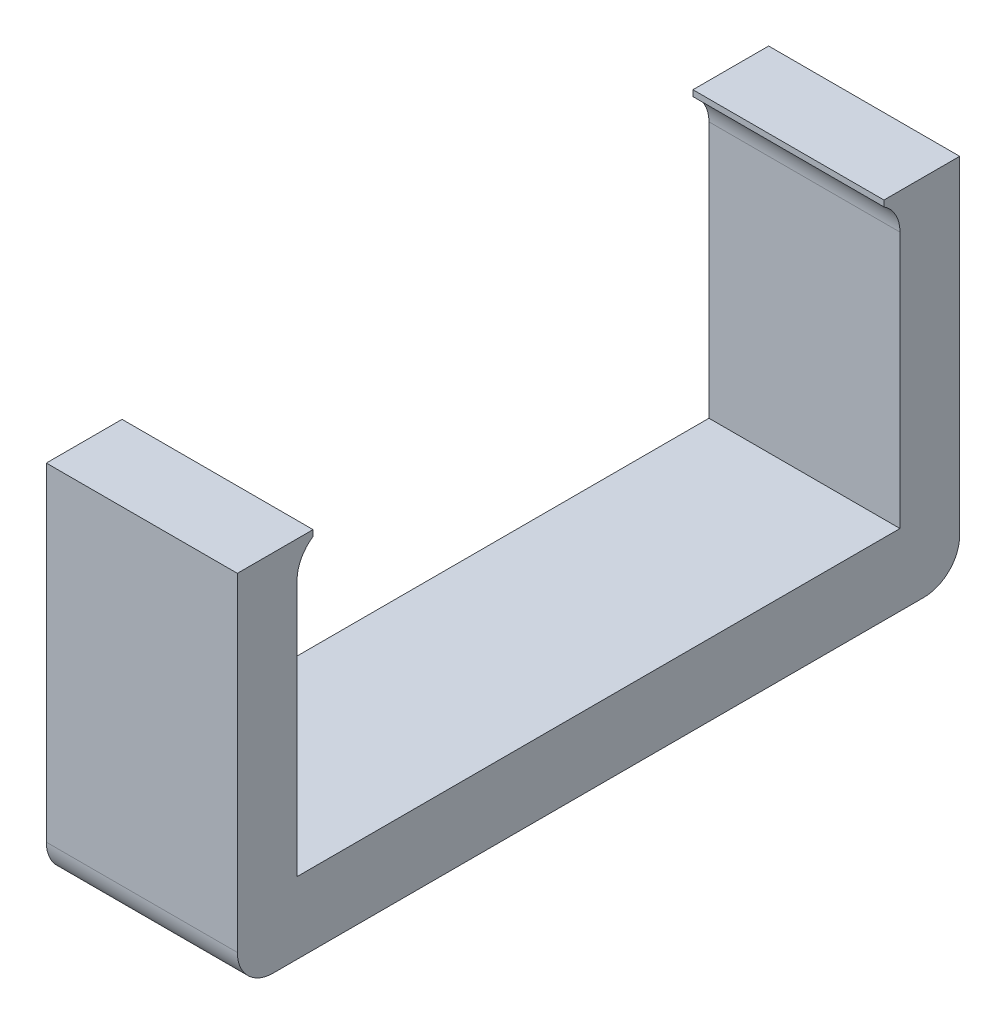
SolidWorks part; units mm, degrees
ref_plane "Front Plane" through (0, 0, 0) normal (0, 0, 1) x (1, 0, 0)
ref_plane "Top Plane" through (0, 0, 0) normal (0, 1, 0) x (1, 0, 0)
ref_plane "Right Plane" through (0, 0, 0) normal (1, 0, 0) x (0, 0, -1)
sketch "Sketch2" plane through (0, 0, 0) normal (1, 0, 0) x (0, 0, -1)
  line L0 (1.5, 0) -> (28.75, 0)
  line L1 (30.25, 1.5) -> (30.25, 15.25)
  line L2 (30.25, 15.25) -> (27.0792, 15.25)
  line L4 (27.75, 3) -> (2.5, 3)
  line L6 (3.1708, 15.25) -> (0, 15.25)
  line L7 (0, 15.25) -> (0, 1.5)
  line L8 (2.5, 3) -> (2.5, 13.75)
  line L9 (27.75, 3) -> (27.75, 13.75)
  line L10 (3.1708, 15.25) -> (3.1708, 15)
  line L11 (27.0792, 15.25) -> (27.0792, 15)
  arc A0 (28.75, 0) -> (30.25, 1.5) centre (28.75, 1.5) ccw
  arc A1 (1.5, 0) -> (0, 1.5) centre (1.5, 1.5) cw
  arc A2 (2.5, 13.75) -> (3.1708, 15) centre (4, 13.75) cw
  arc A3 (27.75, 13.75) -> (27.0792, 15) centre (26.25, 13.75) ccw
  point P11 (30.25, 0)
  point P14 (0, 0)
  dimension "D5" = 1.5
  dimension "D1" = 15.25
  dimension "D2" = 3
  dimension "D3" = 30.25
  dimension "D4" = 1.5
  dimension "D6" = 2.5
  dimension "D8" = 2.5
  dimension "D9" = 25.25
  dimension "D10" = 12.25
  dimension "D11" = 0.25
  dimension "D7" = 3.1708
extrude "ProfileBoss-Extrude1" add sketch "Sketch2" along normal blind 8
equation "\"SerratedChannelWidth\"= 25mm"
equation "\"D3@Sketch2\"=\"SerratedChannelWidth\" + \"SerratedChannelChannelProngWidth\" * 2 + .25mm"
equation "\"SerratedChannelHeight\"= 12.5mm"
equation "\"D1@Sketch2\"=\"SerratedChannelHeight\" + \"SerratedChannelChannelProngWidth\" + .25mm"
equation "\"SerratedChannelBaseHeight\"= 3mm"
equation "\"D2@Sketch2\"=\"SerratedChannelBaseHeight\""
equation "\"SerratedChannelChannelProngWidth\"= 2.5mm"
equation "\"SerratedChannelLength\"= \"SerratedChannelProngClosedWidth\" + \"SerratedChannelProngOpenningWidth\""
equation "\"D1@ProfileBoss-Extrude1\"=\"SerratedChannelLength\""
equation "\"SerratedChannelProngOpenningWidth\"= 3mm"
equation "\"SerratedChannelProngBaseHeight\"= 4mm"
equation "\"SerratedChannelProngHookSize\"= 1.5mm"
equation "\"SerratedChannelProngClosedWidth\"= 5mm"
equation "\"D4@Sketch2\"=\"SerratedChannelBaseHeight\"/2"
equation "\"D6@Sketch2\"=\"SerratedChannelChannelProngWidth\""
equation "\"D8@Sketch2\"=\"SerratedChannelChannelProngWidth\""
